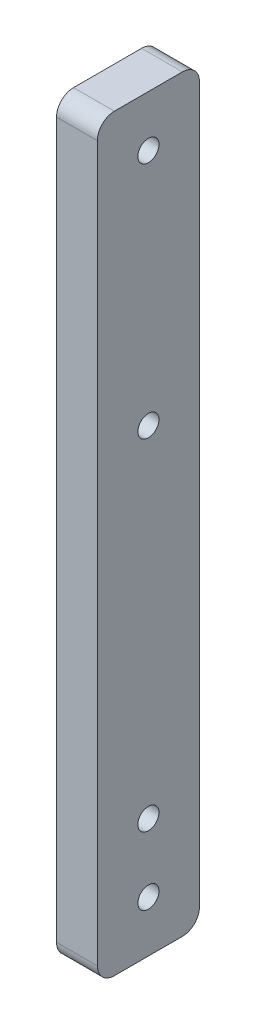
SolidWorks part; units mm, degrees
ref_plane "Front Plane" through (0, 0, 0) normal (0, 0, 1) x (1, 0, 0)
ref_plane "Top Plane" through (0, 0, 0) normal (0, 1, 0) x (1, 0, 0)
ref_plane "Right Plane" through (0, 0, 0) normal (1, 0, 0) x (0, 0, -1)
sketch "Sketch1" plane through (0, 0, 0) normal (1, 0, 0) x (0, 0, -1)
  line L0 (10, 0) -> (10, 190) construction
  line L1 (-10, 190) -> (-10, 0) construction
  line L2 (0, 190) -> (0, 205) construction
  line L3 (-15, 205) -> (15, 205)
  line L4 (-15, 205) -> (-15, -15)
  line L5 (-15, -15) -> (15, -15)
  line L6 (15, 205) -> (15, -15)
  line L7 (0, 190) -> (15, 190) construction
  line L8 (0, 190) -> (-15, 190) construction
  line L9 (0, 0) -> (0, -15) construction
  circle A0 centre (0, 0) radius 3.1
  circle A1 centre (0, 20) radius 3.1
  circle A2 centre (0, 120) radius 3.1
  circle A3 centre (0, 190) radius 3.1
  arc A4 (10, 190) -> (-10, 190) centre (0, 190) ccw construction
  arc A5 (-10, 0) -> (10, 0) centre (0, 0) ccw construction
  point P17 (-17.9074, 207.9074)
  dimension "D1" = 6.2
  dimension "D5" = 10
  dimension "D2" = 20
  dimension "D3" = 100
  dimension "D4" = 70
  dimension "D6" = 15
extrude "Boss-Extrude1" add sketch "Sketch1" along normal blind 12 contours L1 A5 L0 A4
fillet "Fillet1" radius 5 4 edges at (6, -15, 15) (6, -15, -15) (6, 205, 15) (6, 205, -15)
